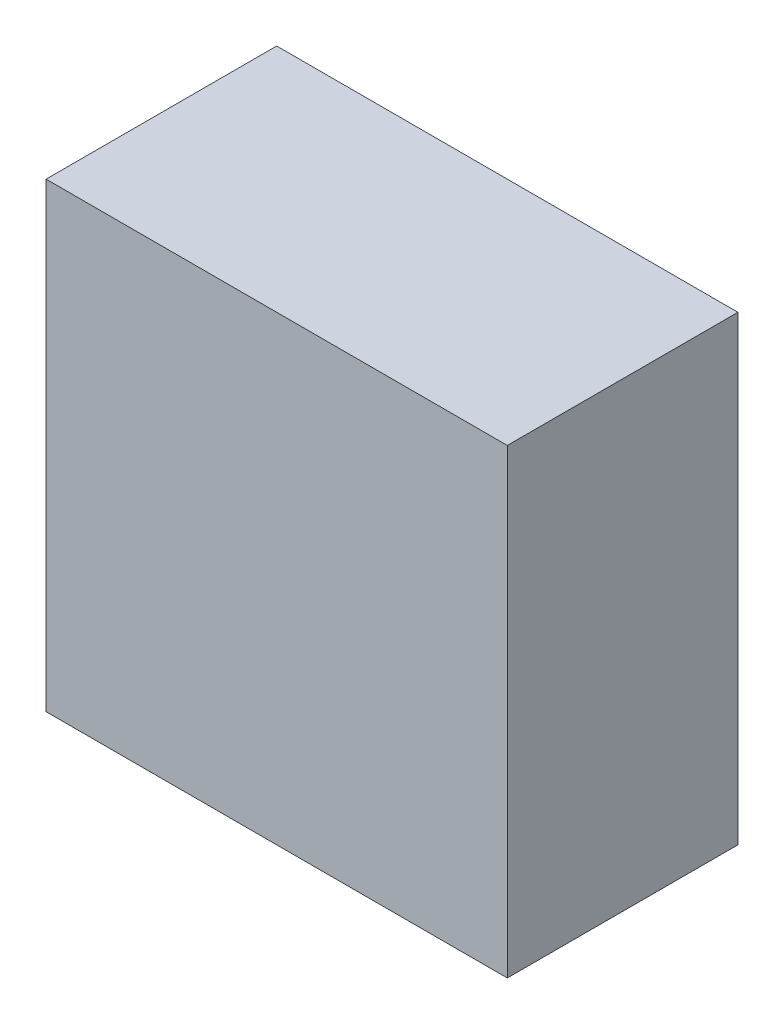
SolidWorks part; units mm, degrees
ref_plane "Płaszczyzna przednia" through (0, 0, 0) normal (0, 0, 1) x (1, 0, 0)
ref_plane "Płaszczyzna górna" through (0, 0, 0) normal (0, 1, 0) x (1, 0, 0)
ref_plane "Płaszczyzna prawa" through (0, 0, 0) normal (1, 0, 0) x (0, 0, -1)
sketch "Szkic1" plane through (0, 0, 0) normal (0, 0, 1) x (1, 0, 0)
  line L1 (-107.8652, 91.573) -> (92.1348, 91.573)
  line L2 (-107.8652, 91.573) -> (-107.8652, -108.427)
  line L3 (-107.8652, -108.427) -> (92.1348, -108.427)
  line L4 (92.1348, 91.573) -> (92.1348, -108.427)
  dimension "D1" = 200
  dimension "D2" = 200
extrude "Dodanie-wyciągnięcie1" add sketch "Szkic1" along normal blind 100
